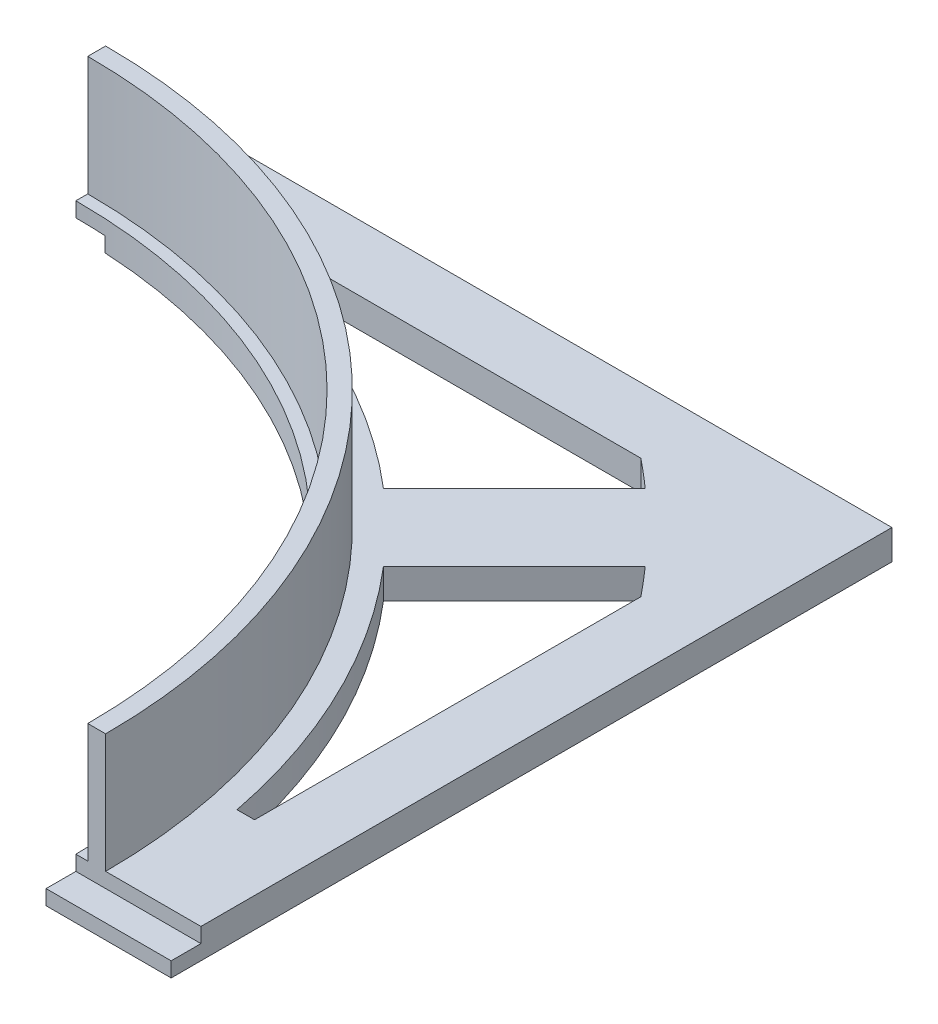
SolidWorks part; units mm, degrees
ref_plane "정면" through (0, 0, 0) normal (0, 0, 1) x (1, 0, 0)
ref_plane "윗면" through (0, 0, 0) normal (0, 1, 0) x (1, 0, 0)
ref_plane "우측면" through (0, 0, 0) normal (1, 0, 0) x (0, 0, -1)
sketch "스케치1" plane through (0, 0, 0) normal (0, 1, 0) x (1, 0, 0)
  line L0 (0, 95) -> (0, 116)
  line L1 (0, 116) -> (116, 116)
  line L2 (116, 116) -> (116, 0)
  line L3 (116, 0) -> (95, 0)
  arc A1 (95, 0) -> (0, 95) centre (0, 0) ccw
  dimension "D1" = 116
  dimension "D2" = 95
  dimension "D3" = 116
extrude "보스-돌출1" add sketch "스케치1" along normal blind 5
sketch "스케치2" plane through (0, 5, 0) normal (0, 1, 0) x (1, 0, 0)
  line L2 (97, 0) -> (100, 0)
  line L3 (0, 100) -> (0, 97)
  line L4 (0, 116) -> (0, 95) construction
  arc A0 (97, 0) -> (0, 97) centre (0, 0) ccw
  arc A1 (100, 0) -> (0, 100) centre (0, 0) ccw
  dimension "D1" = 194
  dimension "D2" = 200
extrude "보스-돌출2" add sketch "스케치2" along normal blind 20
sketch "스케치3" plane through (0, 5, 0) normal (0, 1, 0) x (1, 0, 0)
  line L0 (20, 105) -> (84.8528, 105)
  line L1 (105, 84.8528) -> (105, 20)
  line L2 (105, 20) -> (102.0588, 20)
  line L3 (20, 105) -> (20, 102.0588)
  line L4 (100, 0) -> (116, 0) construction
  line L5 (0, 116) -> (0, 100) construction
  line L6 (78.9781, 67.6644) -> (100.9485, 89.6348)
  line L8 (67.6644, 78.9781) -> (89.6348, 100.9485)
  line L9 (0, 0) -> (116, 116) construction
  arc A0 (102.0588, 20) -> (78.9781, 67.6644) centre (0, 0) ccw
  arc A1 (105, 84.8528) -> (100.9485, 89.6348) centre (0, 0) ccw
  arc A2 (67.6644, 78.9781) -> (20, 102.0588) centre (0, 0) ccw
  arc A3 (89.6348, 100.9485) -> (84.8528, 105) centre (0, 0) ccw
  point P1 (103.5294, 20)
  dimension "D1" = 104
  dimension "D6" = 270
  dimension "D2" = 20
  dimension "D3" = 20
  dimension "D4" = 105
  dimension "D5" = 105
  dimension "D7" = 16
extrude "컷-돌출1" cut sketch "스케치3" against normal through all
sketch "스케치5" plane through (0, 0, 0) normal (0, -1, 0) x (1, 0, 0)
  line L0 (0, -95) -> (0, -116)
  line L1 (0, -116) -> (5, -116)
  line L2 (116, -116) -> (0, -116) construction
  line L3 (5, -116) -> (5, -94.8683)
  line L4 (5, -94.8683) -> (0, -95)
  arc A0 (0, -95) -> (95, 0) centre (0, 0) ccw construction
  dimension "D1" = 5
extrude "컷-돌출2" cut sketch "스케치5" against normal blind 2.5
sketch "스케치6" plane through (0, 0, 0) normal (0, 1, 0) x (1, 0, 0)
  line L0 (95, 0) -> (95, -5)
  line L1 (95, -5) -> (116, -5)
  line L2 (116, -5) -> (116, 0)
  line L3 (116, 0) -> (95, 0)
  dimension "D1" = 5
extrude "보스-돌출3" add sketch "스케치6" along normal blind 2.5
